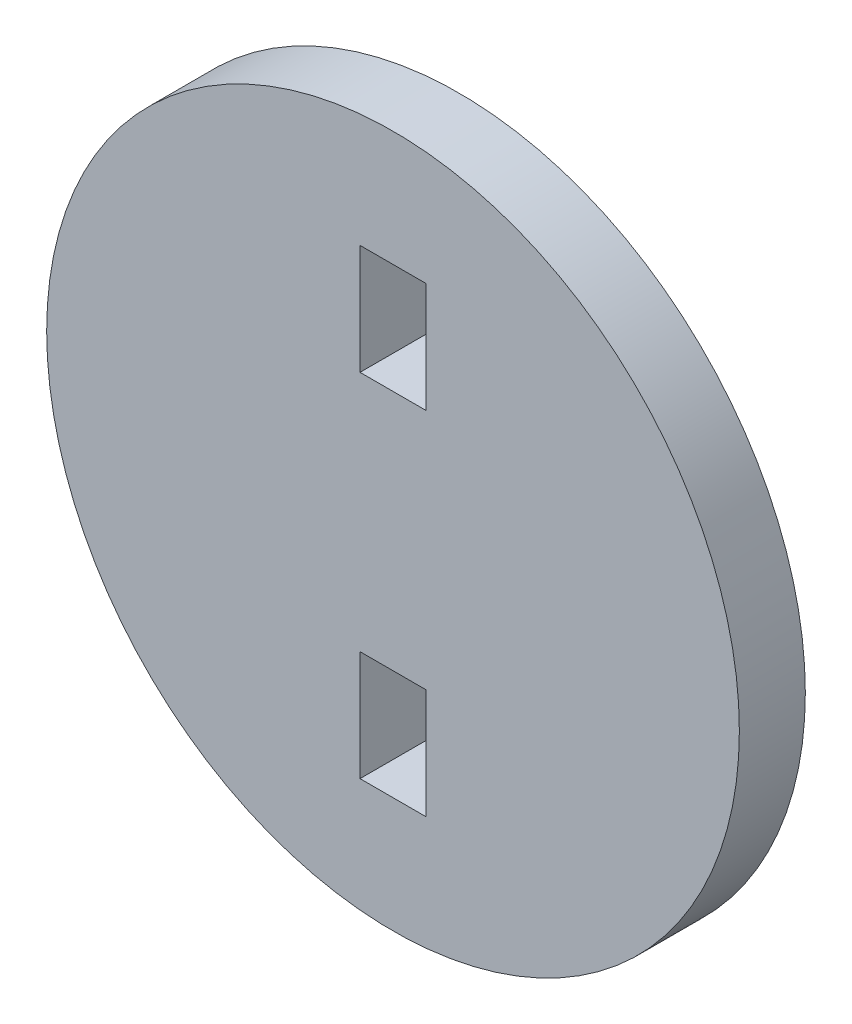
SolidWorks part; units mm, degrees
ref_plane "Plan de face" through (0, 0, 0) normal (0, 0, 1) x (1, 0, 0)
ref_plane "Plan de dessus" through (0, 0, 0) normal (0, 1, 0) x (1, 0, 0)
ref_plane "Plan de droite" through (0, 0, 0) normal (1, 0, 0) x (0, 0, -1)
sketch "Esquisse1" plane through (0, 0, 0) normal (0, 0, 1) x (1, 0, 0)
  line L0 (0, 15.75) -> (0, -15.75) construction
  line L2 (-1.5, 5.5) -> (1.5, 5.5)
  line L3 (-1.5, 5.5) -> (-1.5, 10.5)
  line L4 (-1.5, 10.5) -> (1.5, 10.5)
  line L5 (1.5, 5.5) -> (1.5, 10.5)
  line L6 (1.5, -5.5) -> (-1.5, -5.5)
  line L7 (1.5, -5.5) -> (1.5, -10.5)
  line L8 (1.5, -10.5) -> (-1.5, -10.5)
  line L9 (-1.5, -5.5) -> (-1.5, -10.5)
  circle A0 centre (0, 0) radius 15.75
  dimension "D1" = 1.5
  dimension "D2" = 5
  dimension "D3" = 3
  dimension "D4" = 3
  dimension "D5" = 1.5
  dimension "D6" = 11
  dimension "D7" = 5.5
  dimension "D8" = 5
extrude "Boss.-Extru.1" add sketch "Esquisse1" along normal blind 3
